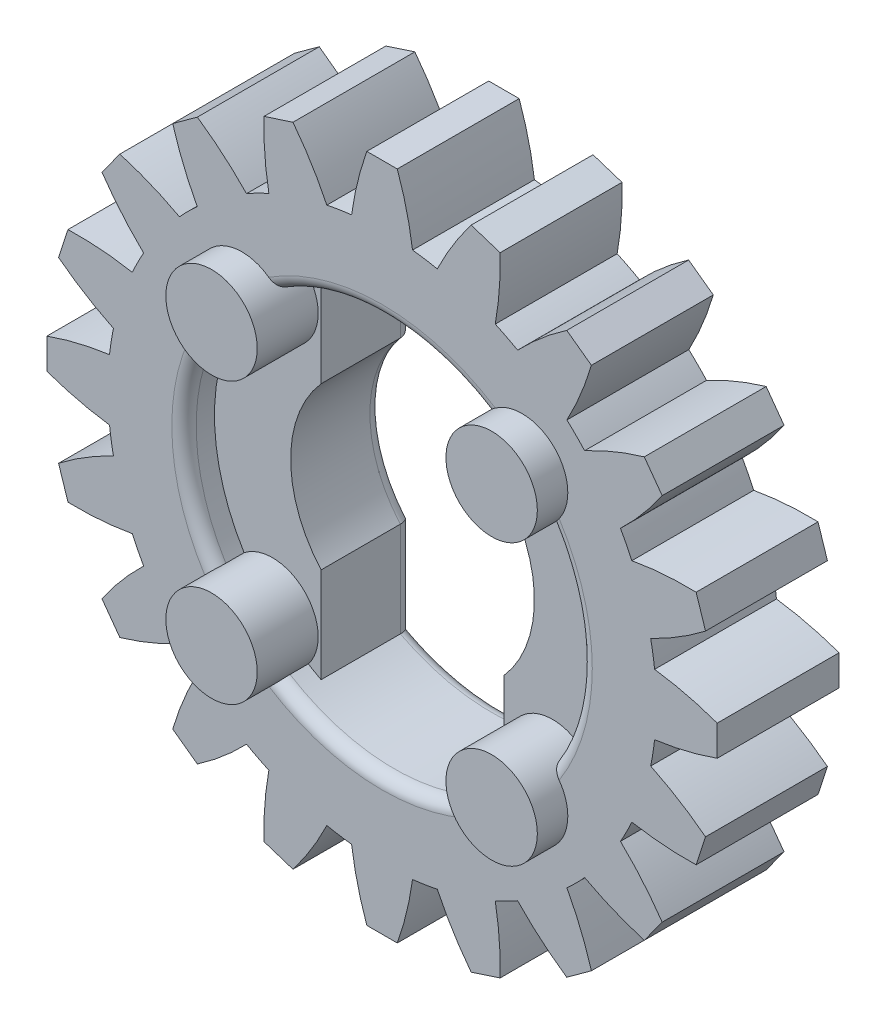
SolidWorks part; units mm, degrees
ref_plane "前视基准面" through (0, 0, 0) normal (0, 0, 1) x (1, 0, 0)
ref_plane "上视基准面" through (0, 0, 0) normal (0, 1, 0) x (1, 0, 0)
ref_plane "右视基准面" through (0, 0, 0) normal (1, 0, 0) x (0, 0, -1)
sketch "草图1" plane through (0, 0, 0) normal (0, 0, 1) x (1, 0, 0)
  circle A0 centre (0, 0) radius 4.5
extrude "凸台-拉伸1" add sketch "草图1" along normal blind 2
sketch "草图4" plane through (0, 0, 2) normal (0, 0, 1) x (1, 0, 0)
  circle A0 centre (0, 0) radius 3.25
  dimension "D1" = 6.5
extrude "切除-拉伸3" cut sketch "草图4" against normal blind 0.5
sketch "草图3" plane through (0, 0, 2) normal (0, 0, 1) x (1, 0, 0)
  line L0 (-1.5, -1.3229) -> (-1.5, -2.8831)
  line L1 (1.5, -1.3229) -> (1.5, -2.8831)
  line L2 (-1.5, 2.8831) -> (-1.5, 1.3229)
  line L4 (1.5, 2.8831) -> (1.5, 1.3229)
  arc A0 (-1.5, 1.3229) -> (-1.5, -1.3229) centre (0, 0) ccw
  arc A1 (-1.5, -2.8831) -> (1.5, -2.8831) centre (0, 0) ccw
  arc A2 (1.5, -1.3229) -> (1.5, 1.3229) centre (0, 0) ccw
  arc A3 (1.5, 2.8831) -> (-1.5, 2.8831) centre (0, 0) ccw
extrude "切除-拉伸1" cut sketch "草图3" against normal through all
sketch "草图2" plane through (0, 0, 2) normal (0, 0, 1) x (1, 0, 0)
  line L0 (1.9374, 5.1536) -> (1.4618, 5.3081)
  line L1 (3.4351, 4.3026) -> (3.0306, 4.5965)
  line L2 (4.5965, 3.0306) -> (4.3026, 3.4351)
  line L3 (5.3081, 1.4618) -> (5.1536, 1.9374)
  line L4 (0.25, 5.5) -> (-0.25, 5.5)
  line L5 (5.5, -0.25) -> (5.5, 0.25)
  line L6 (5.1536, -1.9374) -> (5.3081, -1.4618)
  line L7 (4.3026, -3.4351) -> (4.5965, -3.0306)
  line L8 (3.0306, -4.5965) -> (3.4351, -4.3026)
  line L9 (1.4618, -5.3081) -> (1.9374, -5.1536)
  line L10 (-0.25, -5.5) -> (0.25, -5.5)
  line L11 (-1.9374, -5.1536) -> (-1.4618, -5.3081)
  line L12 (-3.4351, -4.3026) -> (-3.0306, -4.5965)
  line L13 (-4.5965, -3.0306) -> (-4.3026, -3.4351)
  line L14 (-5.3081, -1.4618) -> (-5.1536, -1.9374)
  line L15 (-5.5, 0.25) -> (-5.5, -0.25)
  line L16 (-5.1536, 1.9374) -> (-5.3081, 1.4618)
  line L17 (-4.3026, 3.4351) -> (-4.5965, 3.0306)
  line L18 (-3.0306, 4.5965) -> (-3.4351, 4.3026)
  line L19 (-1.4618, 5.3081) -> (-1.9374, 5.1536)
  arc A0 (0.5, 4.4721) -> (-0.5, 4.4721) centre (0, 0) ccw
  arc A1 (-0.25, 5.5) -> (-0.5, 4.4721) centre (4.5377, 3.7912) ccw
  arc A2 (0.25, 5.5) -> (0.5, 4.4721) centre (-4.5377, 3.7912) cw
  arc A3 (1.8575, 4.0987) -> (0.9064, 4.4078) centre (0, 0) ccw
  arc A4 (1.4618, 5.3081) -> (0.9064, 4.4078) centre (5.4872, 2.2034) ccw
  arc A5 (1.9374, 5.1536) -> (1.8575, 4.0987) centre (-3.1441, 5.0079) cw
  arc A6 (3.0332, 3.3241) -> (2.2241, 3.9119) centre (0, 0) ccw
  arc A7 (3.0306, 4.5965) -> (2.2241, 3.9119) centre (5.8995, 0.3999) ccw
  arc A8 (3.4351, 4.3026) -> (3.0332, 3.3241) centre (-1.4427, 5.7343) cw
  arc A9 (3.9119, 2.2241) -> (3.3241, 3.0332) centre (0, 0) ccw
  arc A10 (4.3026, 3.4351) -> (3.3241, 3.0332) centre (5.7343, -1.4427) ccw
  arc A11 (4.5965, 3.0306) -> (3.9119, 2.2241) centre (0.3999, 5.8995) cw
  arc A12 (4.4078, 0.9064) -> (4.0987, 1.8575) centre (0, 0) ccw
  arc A13 (5.1536, 1.9374) -> (4.0987, 1.8575) centre (5.0079, -3.1441) ccw
  arc A14 (5.3081, 1.4618) -> (4.4078, 0.9064) centre (2.2034, 5.4872) cw
  arc A15 (4.4721, -0.5) -> (4.4721, 0.5) centre (0, 0) ccw
  arc A16 (5.5, 0.25) -> (4.4721, 0.5) centre (3.7912, -4.5377) ccw
  arc A17 (5.5, -0.25) -> (4.4721, -0.5) centre (3.7912, 4.5377) cw
  arc A18 (4.0987, -1.8575) -> (4.4078, -0.9064) centre (0, 0) ccw
  arc A19 (5.3081, -1.4618) -> (4.4078, -0.9064) centre (2.2034, -5.4872) ccw
  arc A20 (5.1536, -1.9374) -> (4.0987, -1.8575) centre (5.0079, 3.1441) cw
  arc A21 (3.3241, -3.0332) -> (3.9119, -2.2241) centre (0, 0) ccw
  arc A22 (4.5965, -3.0306) -> (3.9119, -2.2241) centre (0.3999, -5.8995) ccw
  arc A23 (4.3026, -3.4351) -> (3.3241, -3.0332) centre (5.7343, 1.4427) cw
  arc A24 (2.2241, -3.9119) -> (3.0332, -3.3241) centre (0, 0) ccw
  arc A25 (3.4351, -4.3026) -> (3.0332, -3.3241) centre (-1.4427, -5.7343) ccw
  arc A26 (3.0306, -4.5965) -> (2.2241, -3.9119) centre (5.8995, -0.3999) cw
  arc A27 (0.9064, -4.4078) -> (1.8575, -4.0987) centre (0, 0) ccw
  arc A28 (1.9374, -5.1536) -> (1.8575, -4.0987) centre (-3.1441, -5.0079) ccw
  arc A29 (1.4618, -5.3081) -> (0.9064, -4.4078) centre (5.4872, -2.2034) cw
  arc A30 (-0.5, -4.4721) -> (0.5, -4.4721) centre (0, 0) ccw
  arc A31 (0.25, -5.5) -> (0.5, -4.4721) centre (-4.5377, -3.7912) ccw
  arc A32 (-0.25, -5.5) -> (-0.5, -4.4721) centre (4.5377, -3.7912) cw
  arc A33 (-1.8575, -4.0987) -> (-0.9064, -4.4078) centre (0, 0) ccw
  arc A34 (-1.4618, -5.3081) -> (-0.9064, -4.4078) centre (-5.4872, -2.2034) ccw
  arc A35 (-1.9374, -5.1536) -> (-1.8575, -4.0987) centre (3.1441, -5.0079) cw
  arc A36 (-3.0332, -3.3241) -> (-2.2241, -3.9119) centre (0, 0) ccw
  arc A37 (-3.0306, -4.5965) -> (-2.2241, -3.9119) centre (-5.8995, -0.3999) ccw
  arc A38 (-3.4351, -4.3026) -> (-3.0332, -3.3241) centre (1.4427, -5.7343) cw
  arc A39 (-3.9119, -2.2241) -> (-3.3241, -3.0332) centre (0, 0) ccw
  arc A40 (-4.3026, -3.4351) -> (-3.3241, -3.0332) centre (-5.7343, 1.4427) ccw
  arc A41 (-4.5965, -3.0306) -> (-3.9119, -2.2241) centre (-0.3999, -5.8995) cw
  arc A42 (-4.4078, -0.9064) -> (-4.0987, -1.8575) centre (0, 0) ccw
  arc A43 (-5.1536, -1.9374) -> (-4.0987, -1.8575) centre (-5.0079, 3.1441) ccw
  arc A44 (-5.3081, -1.4618) -> (-4.4078, -0.9064) centre (-2.2034, -5.4872) cw
  arc A45 (-4.4721, 0.5) -> (-4.4721, -0.5) centre (0, 0) ccw
  arc A46 (-5.5, -0.25) -> (-4.4721, -0.5) centre (-3.7912, 4.5377) ccw
  arc A47 (-5.5, 0.25) -> (-4.4721, 0.5) centre (-3.7912, -4.5377) cw
  arc A48 (-4.0987, 1.8575) -> (-4.4078, 0.9064) centre (0, 0) ccw
  arc A49 (-5.3081, 1.4618) -> (-4.4078, 0.9064) centre (-2.2034, 5.4872) ccw
  arc A50 (-5.1536, 1.9374) -> (-4.0987, 1.8575) centre (-5.0079, -3.1441) cw
  arc A51 (-3.3241, 3.0332) -> (-3.9119, 2.2241) centre (0, 0) ccw
  arc A52 (-4.5965, 3.0306) -> (-3.9119, 2.2241) centre (-0.3999, 5.8995) ccw
  arc A53 (-4.3026, 3.4351) -> (-3.3241, 3.0332) centre (-5.7343, -1.4427) cw
  arc A54 (-2.2241, 3.9119) -> (-3.0332, 3.3241) centre (0, 0) ccw
  arc A55 (-3.4351, 4.3026) -> (-3.0332, 3.3241) centre (1.4427, 5.7343) ccw
  arc A56 (-3.0306, 4.5965) -> (-2.2241, 3.9119) centre (-5.8995, 0.3999) cw
  arc A57 (-0.9064, 4.4078) -> (-1.8575, 4.0987) centre (0, 0) ccw
  arc A58 (-1.9374, 5.1536) -> (-1.8575, 4.0987) centre (3.1441, 5.0079) ccw
  arc A59 (-1.4618, 5.3081) -> (-0.9064, 4.4078) centre (-5.4872, 2.2034) cw
  point P125 (0, 0)
  dimension "D1" = 20
extrude "凸台-拉伸2" add sketch "草图2" against normal blind 2
fillet "圆角1" radius 0.2 9 edges at (-1.5, 2.103, 0) (0, 3.25, 0) (1.5, 2.103, 0) (2, 0, 0) (1.5, -2.103, 0) (0, -3.25, 0) (-1.5, -2.103, 0) (-2, 0, 0) (3.25, 0, 2)
sketch "草图5" plane through (0, 0, 2) normal (0, 0, 1) x (1, 0, 0)
  line L0 (0, 0) -> (0, 3.25) construction
  line L1 (0, 0) -> (0, -3.45) construction
  line L2 (0, 0) -> (-3.25, 0) construction
  line L3 (0, 0) -> (3.25, 0) construction
  line L4 (0, 0) -> (-2.2981, 2.2981) construction
  circle A0 centre (0, 0) radius 3.25 construction
  circle A1 centre (0, 0) radius 3.45 construction
  circle A2 centre (-2.2981, 2.2981) radius 0.75
  circle A3 centre (2.2981, 2.2981) radius 0.75
  circle A4 centre (2.2981, -2.2981) radius 0.75
  circle A5 centre (-2.2981, -2.2981) radius 0.75
  point P21 (0, 0)
  dimension "D1" = 6.5
  dimension "D3" = 1.5
  dimension "D2" = 45
  dimension "D4" = 4
extrude "凸台-拉伸3" add sketch "草图5" along normal blind 0.5 and the other way blind 1
